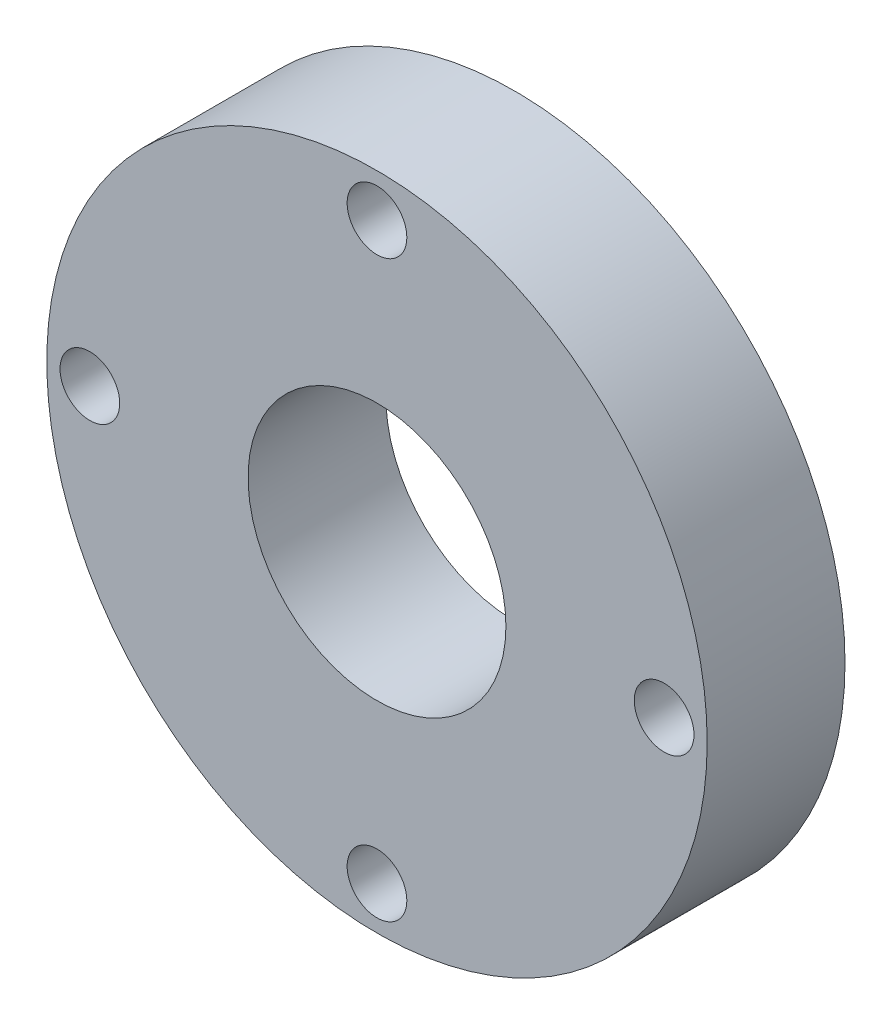
SolidWorks part; units mm, degrees
material "6061-T6 (SS)"
ref_plane "Front Plane" through (0, 0, 0) normal (0, 0, 1) x (1, 0, 0)
ref_plane "Top Plane" through (0, 0, 0) normal (0, 1, 0) x (1, 0, 0)
ref_plane "Right Plane" through (0, 0, 0) normal (1, 0, 0) x (0, 0, -1)
sketch "Sketch1" plane through (0, 0, 0) normal (1, 0, 0) x (0, 0, -1)
  line L0 (-95.847, -9.525) -> (-140.95, -9.525)
  line L5 (-1000, 0) -> (49000, 0)
  line L6 (0, -9.525) -> (0, 9.525)
  line L13 (0, 9.525) -> (-45.847, 9.525)
  line L26 (-45.847, 9.525) -> (-45.847, 14)
  line L27 (-45.847, 14) -> (-95.847, 14)
  line L32 (-95.847, 14) -> (-95.847, 9.525)
  line L34 (-160, 7) -> (-160, -7)
  line L36 (-95.847, -9.525) -> (-95.847, -14)
  line L37 (-95.847, -14) -> (-45.847, -14)
  line L38 (-45.847, -14) -> (-45.847, -9.525)
  line L39 (0, -9.525) -> (-45.847, -9.525)
  line L40 (-25.305, 36.5125) -> (-16.305, 36.5125)
  line L41 (-111.341, 22.6187) -> (-95.847, 22.6187)
  line L42 (-111.341, 22.6187) -> (-111.341, -22.6187)
  line L43 (-111.341, -22.6187) -> (-95.847, -22.6187)
  line L44 (-95.847, 22.6187) -> (-95.847, -22.6187)
  line L45 (-111.341, 22.6187) -> (-95.847, -22.6187) construction
  line L46 (-111.341, -22.6187) -> (-95.847, 22.6187) construction
  line L47 (-30.353, 22.6187) -> (-45.847, 22.6187)
  line L48 (-30.353, 22.6187) -> (-30.353, -22.6187)
  line L49 (-30.353, -22.6187) -> (-45.847, -22.6187)
  line L50 (-45.847, 22.6187) -> (-45.847, -22.6187)
  line L51 (-30.353, 22.6187) -> (-45.847, -22.6187) construction
  line L52 (-30.353, -22.6187) -> (-45.847, 22.6187) construction
  line L59 (-16.305, 36.5125) -> (-16.305, -36.5125)
  line L60 (-16.305, -36.5125) -> (-25.305, -36.5125)
  line L61 (-25.305, -22.6187) -> (-27.305, -22.6187)
  line L62 (-27.305, -22.6187) -> (-27.305, -12.5)
  line L63 (-27.305, -12.5) -> (-25.305, -12.5)
  line L64 (-25.305, -12.5) -> (-25.305, 12.5)
  line L65 (-25.305, 12.5) -> (-27.305, 12.5)
  line L66 (-27.305, 12.5) -> (-27.305, 22.6187)
  line L67 (-27.305, 22.6187) -> (-25.305, 22.6187)
  line L68 (-25.305, 22.6187) -> (-25.305, 36.5125)
  line L69 (-25.305, -22.6187) -> (-25.305, -36.5125)
  line L71 (-119.469, 36.5125) -> (-26.305, 36.5125)
  line L72 (-119.469, 36.5125) -> (-119.469, -36.5125)
  line L73 (-119.469, -36.5125) -> (-26.305, -36.5125)
  line L74 (-26.305, 36.5125) -> (-26.305, -36.5125)
  line L75 (-119.469, 36.5125) -> (-26.305, -36.5125) construction
  line L76 (-119.469, -36.5125) -> (-26.305, 36.5125) construction
  line L77 (-140.95, -9.525) -> (-140.95, -7)
  line L78 (-140.95, -7) -> (-160, -7)
  line L79 (-95.847, 9.525) -> (-140.95, 9.525)
  line L80 (-140.95, 7) -> (-160, 7)
  line L81 (-140.95, 9.525) -> (-140.95, 7)
  line L82 (-118.3985, 9.525) -> (-118.3985, -9.525) construction
  line L83 (-22.9235, 9.525) -> (-22.9235, -9.525) construction
  line L96 (-119.469, 36.5125) -> (-134.709, 36.5125)
  line L98 (-119.469, -36.5125) -> (-134.709, -36.5125)
  line L99 (-134.709, 36.5125) -> (-134.709, -36.5125)
  line L110 (-119.469, 36.5125) -> (-119.469, -36.5125)
  point P3 (0, 0)
  point P18 (-103.594, 0)
  point P24 (-38.1, 0)
  point P29 (-72.887, 0)
  point P48 (-16.305, 30.5656)
  point P58 (0, 0)
  point P59 (0, 0)
  point P70 (-134.709, 31.75)
revolve "Main_body" add sketch "Sketch1" angle 360 about L5
sketch "Sketch5" plane through (0, 0, 134.709) normal (0, 0, 1) x (1, 0, 0)
  circle A0 centre (0, 0) radius 14.2558
  dimension "D1" = 28.5115
extrude "seal_seat" cut sketch "Sketch5" against normal through all
hole_wizard "M6 Clearance Hole1" positions "Sketch3" profile "Sketch4" hole size "M6" standard "ANSI Metric" end condition through all
sketch "Sketch3" plane through (0, 0, 134.709) normal (0, 0, 1) x (1, 0, 0)
  point P0 (0, 31.75)
sketch "Sketch4" plane through (0, 31.75, 134.709) normal (1, 0, 0) x (0, -1, 0)
  line L0 (0, 0) -> (0, 15.24)
  line L1 (0, 15.24) -> (3.3, 15.24)
  line L2 (3.3, 15.24) -> (3.3, 0)
  line L5 (3.3, 0) -> (0, 0)
  line L11 (0, -6.35) -> (0, 107.95) construction
  dimension "Thru Hole Dia." = 6.6
  dimension "Thru Hole Depth" = 15.24
pattern_circular "CirPattern1" count 4 over 360 about axis through (0, 0, 0) along (0, 0, 1) of "M6 Clearance Hole1"
